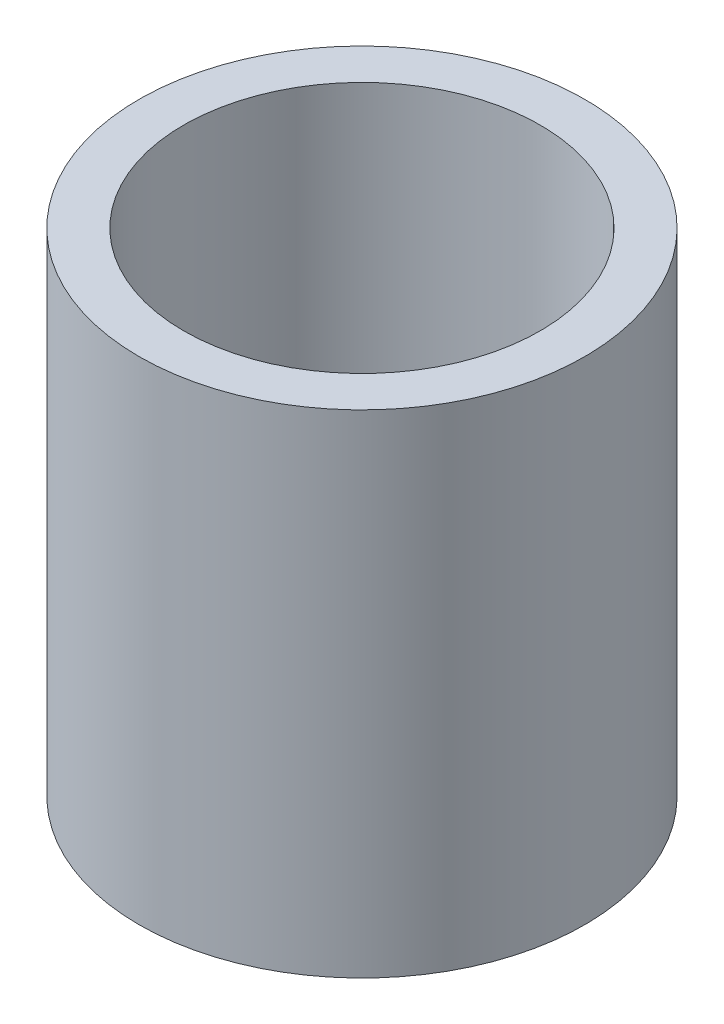
SolidWorks part; units mm, degrees
ref_plane "Front Plane" through (0, 0, 0) normal (0, 0, 1) x (1, 0, 0)
ref_plane "Top Plane" through (0, 0, 0) normal (0, 1, 0) x (1, 0, 0)
ref_plane "Right Plane" through (0, 0, 0) normal (1, 0, 0) x (0, 0, -1)
sketch "Sketch2" plane through (0, 0, 0) normal (0, 1, 0) x (1, 0, 0)
  circle A0 centre (0, 0) radius 0.5
  circle A1 centre (0, 0) radius 0.625
  dimension "D1" = 1.25
  dimension "D2" = 1
extrude "Boss-Extrude1" add sketch "Sketch2" along normal mid plane 1.38
